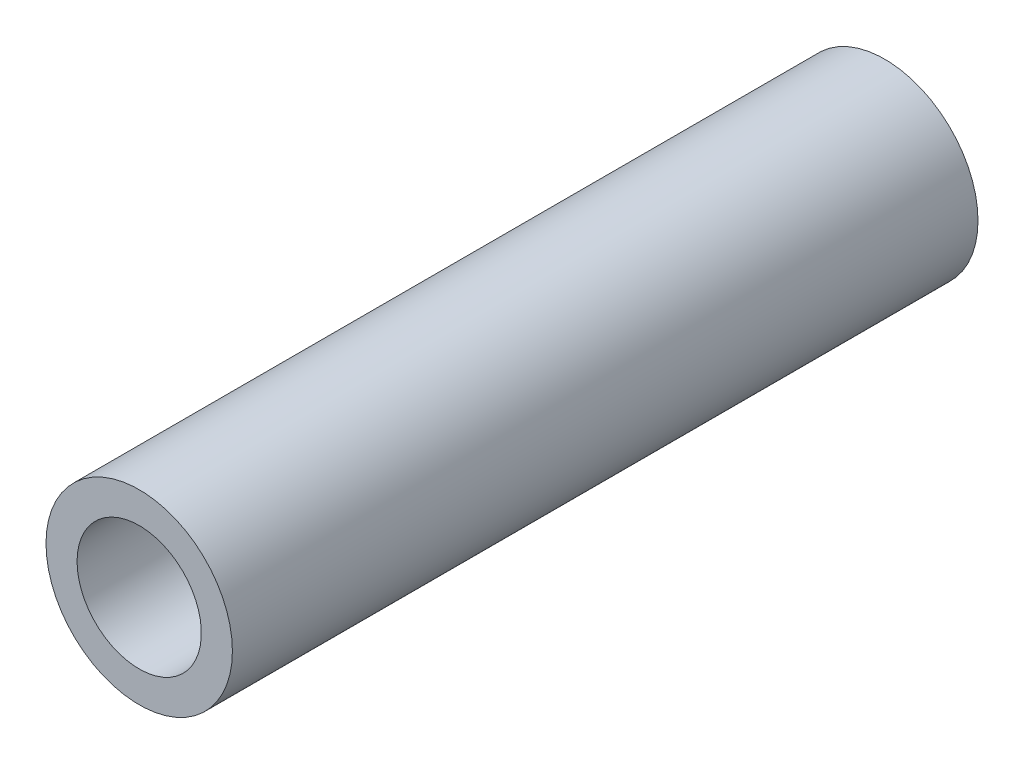
SolidWorks part; units mm, degrees
ref_plane "Front" through (0, 0, 0) normal (0, 0, 1) x (1, 0, 0)
ref_plane "Top" through (0, 0, 0) normal (0, 1, 0) x (1, 0, 0)
ref_plane "Right" through (0, 0, 0) normal (1, 0, 0) x (0, 0, -1)
sketch "Sketch1" plane through (0, 0, 0) normal (0, 0, 1) x (1, 0, 0)
  circle A0 centre (0, 0) radius 1.5875
  circle A1 centre (0, 0) radius 2.3813
  dimension "D1" = 3.175
  dimension "D2" = 4.7625
extrude "Boss-Extrude1" add sketch "Sketch1" along normal blind 19.05
